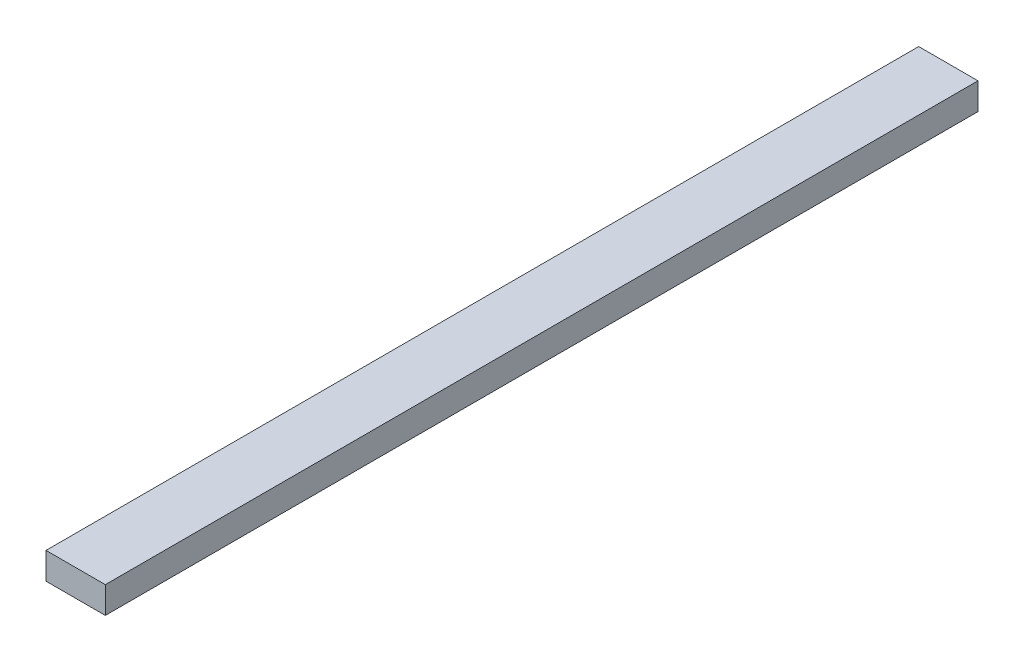
SolidWorks part; units mm, degrees
material "AA356.0-F"
ref_plane "Front Plane" through (0, 0, 0) normal (0, 0, 1) x (1, 0, 0)
ref_plane "Top Plane" through (0, 0, 0) normal (0, 1, 0) x (1, 0, 0)
ref_plane "Right Plane" through (0, 0, 0) normal (1, 0, 0) x (0, 0, -1)
sketch "Sketch2" plane through (0, 0, 0) normal (0, 0, 1) x (1, 0, 0)
  line L1 (-152.5862, 55.6034) -> (-72.5862, 55.6034)
  line L2 (-152.5862, 55.6034) -> (-152.5862, 19.6034)
  line L3 (-152.5862, 19.6034) -> (-72.5862, 19.6034)
  line L4 (-72.5862, 55.6034) -> (-72.5862, 19.6034)
  dimension "D1" = 80
  dimension "3.6" = 36
extrude "Boss-Extrude1" add sketch "Sketch2" along normal blind 1177
